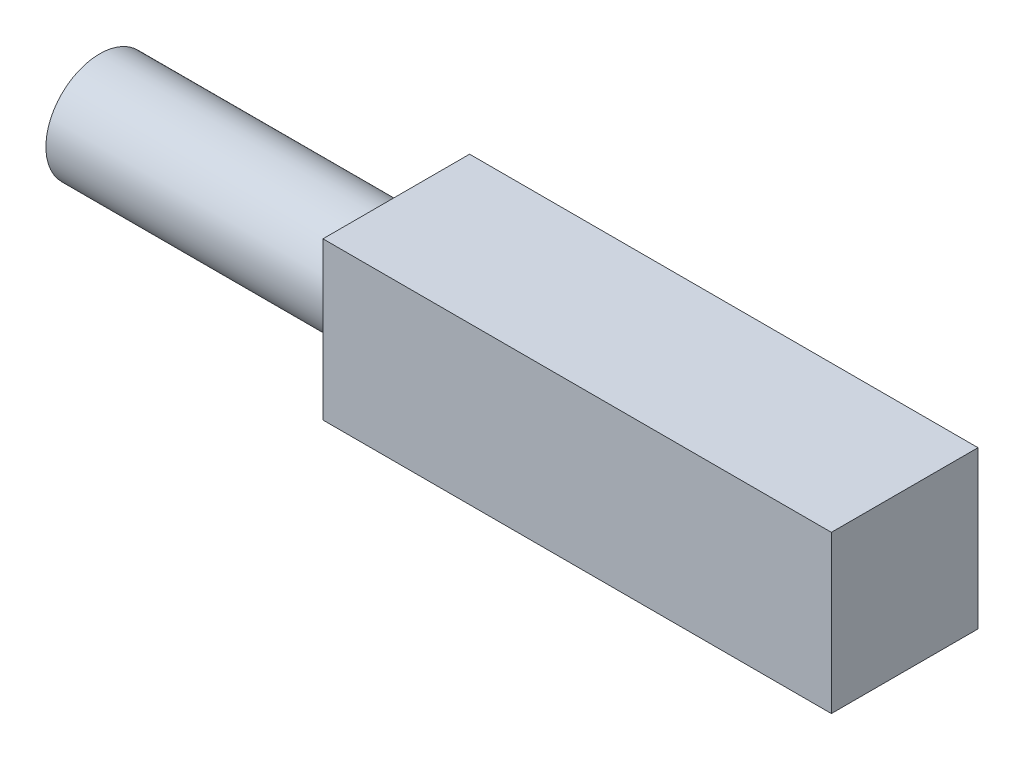
SolidWorks part; units mm, degrees
ref_plane "Front Plane" through (0, 0, 0) normal (1, 0, 0) x (0, 1, 0)
ref_plane "Top Plane" through (0, 0, 0) normal (0, 0, 1) x (0, 1, 0)
ref_plane "Right Plane" through (0, 0, 0) normal (0, 1, 0) x (-1, 0, 0)
sketch "Sketch1" plane through (0, 0, 0) normal (1, 0, 0) x (0, 1, 0)
  circle A0 centre (0, 0) radius 12.7
  dimension "D1" = 25.4
extrude "Boss-Extrude1" add sketch "Sketch1" along normal blind 70
sketch "Sketch2" plane through (70, 0, 0) normal (1, 0, 0) x (0, 1, 0)
  line L1 (-18.5251, -17.3039) -> (18.5251, -17.3039)
  line L2 (-18.5251, -17.3039) -> (-18.5251, 17.3039)
  line L3 (-18.5251, 17.3039) -> (18.5251, 17.3039)
  line L4 (18.5251, -17.3039) -> (18.5251, 17.3039)
  line L5 (-18.5251, -17.3039) -> (18.5251, 17.3039) construction
  line L6 (-18.5251, 17.3039) -> (18.5251, -17.3039) construction
  point P0 (0, 0)
extrude "Boss-Extrude2" add sketch "Sketch2" along normal blind 120
